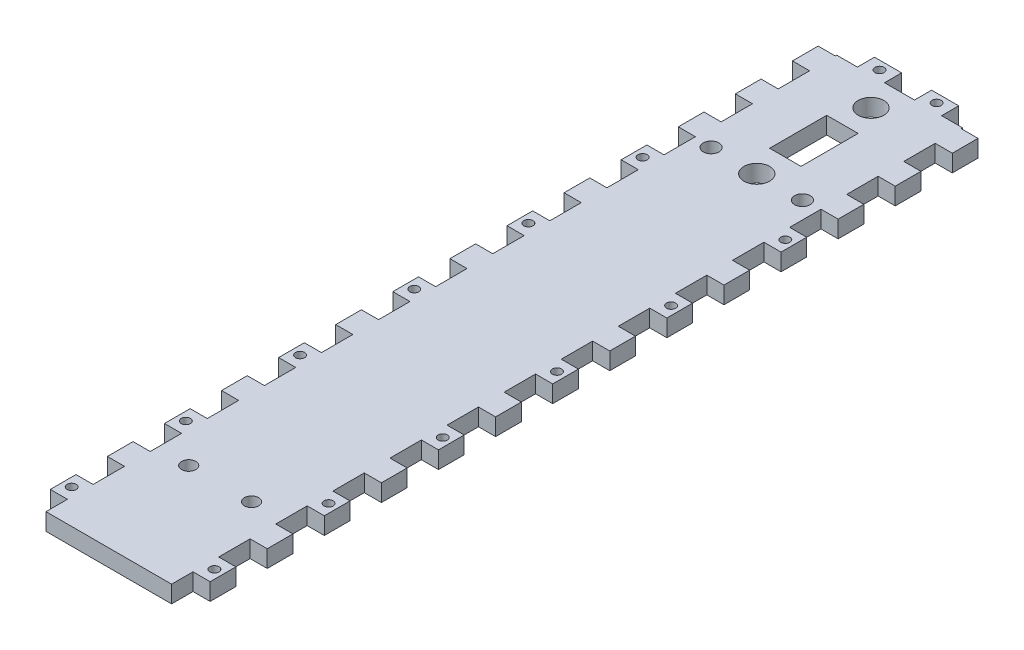
SolidWorks part; units mm, degrees
ref_plane "Plan de face" through (0, 0, 0) normal (0, 0, 1) x (1, 0, 0)
ref_plane "Plan de dessus" through (0, 0, 0) normal (0, 1, 0) x (1, 0, 0)
ref_plane "Plan de droite" through (0, 0, 0) normal (1, 0, 0) x (0, 0, -1)
sketch "Sketch1" plane through (0, 0, 0) normal (0, 1, 0) x (1, 0, 0)
  line L0 (50, 276.5) -> (50, 267.5)
  line L1 (0, 0) -> (44, 0)
  line L2 (0, 0) -> (0, 277)
  line L3 (0, 277) -> (44, 277)
  line L4 (44, 0) -> (44, 277)
  line L5 (0, 276.5) -> (-6, 276.5)
  line L6 (0, 276.5) -> (0, 267.5)
  line L7 (0, 267.5) -> (-6, 267.5)
  line L8 (-6, 276.5) -> (-6, 267.5)
  line L9 (50, 276.5) -> (44, 276.5)
  line L10 (44, 276.5) -> (44, 267.5)
  line L11 (50, 267.5) -> (44, 267.5)
  line L12 (50, 256.5) -> (50, 247.5)
  line L13 (50, 256.5) -> (44, 256.5)
  line L14 (44, 256.5) -> (44, 247.5)
  line L15 (50, 247.5) -> (44, 247.5)
  line L16 (50, 236.5) -> (50, 227.5)
  line L17 (50, 236.5) -> (44, 236.5)
  line L18 (44, 236.5) -> (44, 227.5)
  line L19 (50, 227.5) -> (44, 227.5)
  line L20 (50, 216.5) -> (50, 207.5)
  line L21 (50, 216.5) -> (44, 216.5)
  line L22 (44, 216.5) -> (44, 207.5)
  line L23 (50, 207.5) -> (44, 207.5)
  line L24 (50, 196.5) -> (50, 187.5)
  line L25 (50, 196.5) -> (44, 196.5)
  line L26 (44, 196.5) -> (44, 187.5)
  line L27 (50, 187.5) -> (44, 187.5)
  line L28 (50, 176.5) -> (50, 167.5)
  line L29 (50, 176.5) -> (44, 176.5)
  line L30 (44, 176.5) -> (44, 167.5)
  line L31 (50, 167.5) -> (44, 167.5)
  line L32 (50, 156.5) -> (50, 147.5)
  line L33 (50, 156.5) -> (44, 156.5)
  line L34 (44, 156.5) -> (44, 147.5)
  line L35 (50, 147.5) -> (44, 147.5)
  line L36 (50, 136.5) -> (50, 127.5)
  line L37 (50, 136.5) -> (44, 136.5)
  line L38 (44, 136.5) -> (44, 127.5)
  line L39 (50, 127.5) -> (44, 127.5)
  line L40 (50, 116.5) -> (50, 107.5)
  line L41 (50, 116.5) -> (44, 116.5)
  line L42 (44, 116.5) -> (44, 107.5)
  line L43 (50, 107.5) -> (44, 107.5)
  line L44 (50, 96.5) -> (50, 87.5)
  line L45 (50, 96.5) -> (44, 96.5)
  line L46 (44, 96.5) -> (44, 87.5)
  line L47 (50, 87.5) -> (44, 87.5)
  line L48 (50, 76.5) -> (50, 67.5)
  line L49 (50, 76.5) -> (44, 76.5)
  line L50 (44, 76.5) -> (44, 67.5)
  line L51 (50, 67.5) -> (44, 67.5)
  line L52 (50, 56.5) -> (50, 47.5)
  line L53 (50, 56.5) -> (44, 56.5)
  line L54 (44, 56.5) -> (44, 47.5)
  line L55 (50, 47.5) -> (44, 47.5)
  line L56 (50, 36.5) -> (50, 27.5)
  line L57 (50, 36.5) -> (44, 36.5)
  line L58 (44, 36.5) -> (44, 27.5)
  line L59 (50, 27.5) -> (44, 27.5)
  line L60 (50, 16.5) -> (50, 7.5)
  line L61 (50, 16.5) -> (44, 16.5)
  line L62 (44, 16.5) -> (44, 7.5)
  line L63 (50, 7.5) -> (44, 7.5)
  line L64 (0, 256.5) -> (0, 247.5)
  line L65 (0, 256.5) -> (-6, 256.5)
  line L66 (-6, 256.5) -> (-6, 247.5)
  line L67 (0, 247.5) -> (-6, 247.5)
  line L68 (0, 236.5) -> (0, 227.5)
  line L69 (0, 236.5) -> (-6, 236.5)
  line L70 (-6, 236.5) -> (-6, 227.5)
  line L71 (0, 227.5) -> (-6, 227.5)
  line L72 (0, 216.5) -> (0, 207.5)
  line L73 (0, 216.5) -> (-6, 216.5)
  line L74 (-6, 216.5) -> (-6, 207.5)
  line L75 (0, 207.5) -> (-6, 207.5)
  line L76 (0, 196.5) -> (0, 187.5)
  line L77 (0, 196.5) -> (-6, 196.5)
  line L78 (-6, 196.5) -> (-6, 187.5)
  line L79 (0, 187.5) -> (-6, 187.5)
  line L80 (0, 176.5) -> (0, 167.5)
  line L81 (0, 176.5) -> (-6, 176.5)
  line L82 (-6, 176.5) -> (-6, 167.5)
  line L83 (0, 167.5) -> (-6, 167.5)
  line L84 (0, 156.5) -> (0, 147.5)
  line L85 (0, 156.5) -> (-6, 156.5)
  line L86 (-6, 156.5) -> (-6, 147.5)
  line L87 (0, 147.5) -> (-6, 147.5)
  line L88 (0, 136.5) -> (0, 127.5)
  line L89 (0, 136.5) -> (-6, 136.5)
  line L90 (-6, 136.5) -> (-6, 127.5)
  line L91 (0, 127.5) -> (-6, 127.5)
  line L92 (0, 116.5) -> (0, 107.5)
  line L93 (0, 116.5) -> (-6, 116.5)
  line L94 (-6, 116.5) -> (-6, 107.5)
  line L95 (0, 107.5) -> (-6, 107.5)
  line L96 (0, 96.5) -> (0, 87.5)
  line L97 (0, 96.5) -> (-6, 96.5)
  line L98 (-6, 96.5) -> (-6, 87.5)
  line L99 (0, 87.5) -> (-6, 87.5)
  line L100 (0, 76.5) -> (0, 67.5)
  line L101 (0, 76.5) -> (-6, 76.5)
  line L102 (-6, 76.5) -> (-6, 67.5)
  line L103 (0, 67.5) -> (-6, 67.5)
  line L104 (0, 56.5) -> (0, 47.5)
  line L105 (0, 56.5) -> (-6, 56.5)
  line L106 (-6, 56.5) -> (-6, 47.5)
  line L107 (0, 47.5) -> (-6, 47.5)
  line L108 (0, 36.5) -> (0, 27.5)
  line L109 (0, 36.5) -> (-6, 36.5)
  line L110 (-6, 36.5) -> (-6, 27.5)
  line L111 (0, 27.5) -> (-6, 27.5)
  line L112 (0, 16.5) -> (0, 7.5)
  line L113 (0, 16.5) -> (-6, 16.5)
  line L114 (-6, 16.5) -> (-6, 7.5)
  line L115 (0, 7.5) -> (-6, 7.5)
  line L117 (7.25, 277) -> (16.75, 277)
  line L118 (7.25, 277) -> (7.25, 283)
  line L119 (7.25, 283) -> (16.75, 283)
  line L120 (16.75, 277) -> (16.75, 283)
  line L121 (36.75, 277) -> (27.25, 277)
  line L122 (36.75, 277) -> (36.75, 283)
  line L123 (36.75, 283) -> (27.25, 283)
  line L124 (27.25, 277) -> (27.25, 283)
  dimension "D1" = 277
  dimension "D2" = 44
  dimension "D3" = 9
  dimension "D4" = 6
  dimension "D5" = 0.5
  dimension "D8" = 9.5
  dimension "D9" = 6
  dimension "D10" = 7.25
  dimension "D11" = 9.5
  dimension "D12" = 6
  dimension "D13" = 7.25
  dimension "D6" = 2
  dimension "D7" = 14
extrude "Boss-Extrude1" add sketch "Sketch1" along normal blind 6 contours L1 L4 L3 L2 | L115 L2 L113 L114 | L111 L2 L109 L110 | L107 L2 L105 L106 | L103 L2 L101 L102 | L99 L2 L97 L98 | L95 L2 L93 L94 | L91 L2 L89 L90 | L87 L2 L85 L86 | L83 L2 L81 L82 | L79 L2 L77 L78 | L75 L2 L73 L74 | L71 L2 L69 L70 | L67 L2 L65 L66 | L5 L8 L7 L2 | L3 L120 L119 L118 | L124 L3 L122 L123 | L11 L0 L9 L4 | L15 L12 L13 L4 | L19 L16 L17 L4 | L23 L20 L21 L4 | L27 L24 L25 L4 | L31 L28 L29 L4 | L35 L32 L33 L4 | L39 L36 L37 L4 | L43 L40 L41 L4 | L47 L44 L45 L4 | L51 L48 L49 L4 | L55 L52 L53 L4 | L59 L56 L57 L4 | L63 L60 L61 L4
sketch "Sketch2" plane through (0, 6, 0) normal (0, 1, 0) x (1, 0, 0)
  line L1 (16.5, 257) -> (27.5, 257)
  line L2 (16.5, 257) -> (16.5, 237)
  line L3 (16.5, 237) -> (27.5, 237)
  line L4 (27.5, 257) -> (27.5, 237)
  line L5 (16.75, 277) -> (27.25, 277) construction
  circle A2 centre (22, 267) radius 4.5
  circle A3 centre (22, 227) radius 4.5
  circle A4 centre (6, 227) radius 2.75
  circle A5 centre (38, 227) radius 2.75
  point P0 (24.3317, 226.6409)
  point P3 (22, 277)
  point P15 (22, 257)
  point P20 (-50.7436, 236.2065)
  dimension "D2" = 10
  dimension "D6" = 9
  dimension "D7" = 9
  dimension "D12" = 5.5
  dimension "D13" = 5.5
  dimension "D8" = 40
  dimension "D9" = 11
  dimension "D10" = 10
  dimension "D11" = 10
  dimension "D14" = 32
  dimension "D15" = 16
extrude "Cut-Extrude1" cut sketch "Sketch2" against normal through all both and the other way through all
sketch "Sketch4" plane through (0, 6, 0) normal (0, 1, 0) x (1, 0, 0)
  line L0 (0, 0) -> (44, 0) construction
  line L1 (22, 0) -> (22, 10.4293) construction
  circle A0 centre (33, 39) radius 2.5
  circle A1 centre (11, 39) radius 2.5
  point P6 (22, 0)
  dimension "D1" = 5
  dimension "D2" = 39
  dimension "D3" = 11
extrude "Cut-Extrude3" cut sketch "Sketch4" against normal through all both and the other way through all
sketch "Sketch5" plane through (0, 6, 0) normal (0, 1, 0) x (1, 0, 0)
  line L0 (0, 16.5) -> (-6, 16.5) construction
  line L1 (-6, 16.5) -> (-6, 7.5) construction
  line L2 (7.25, 283) -> (16.75, 283) construction
  line L3 (36.75, 283) -> (27.25, 283) construction
  line L4 (7.25, 277) -> (7.25, 283) construction
  circle A0 centre (-3, 12) radius 1.6
  circle A1 centre (47, 12) radius 1.6
  circle A2 centre (47, 52) radius 1.6
  circle A3 centre (47, 92) radius 1.6
  circle A4 centre (47, 132) radius 1.6
  circle A5 centre (47, 172) radius 1.6
  circle A6 centre (47, 212) radius 1.6
  circle A7 centre (-3, 52) radius 1.6
  circle A8 centre (-3, 92) radius 1.6
  circle A9 centre (-3, 132) radius 1.6
  circle A10 centre (-3, 172) radius 1.6
  circle A11 centre (-3, 212) radius 1.6
  circle A12 centre (32, 280) radius 1.6
  circle A13 centre (12, 280) radius 1.6
  point P5 (-3, 16.5)
  point P9 (-6, 12)
  point P37 (12, 283)
  point P41 (32, 283)
  point P45 (7.25, 280)
  dimension "D1" = 3.2
  dimension "D4" = 3.2
  dimension "D5" = 3.2
  dimension "D2" = 2
  dimension "D3" = 6
extrude "Cut-Extrude4" cut sketch "Sketch5" against normal through all both and the other way through all
